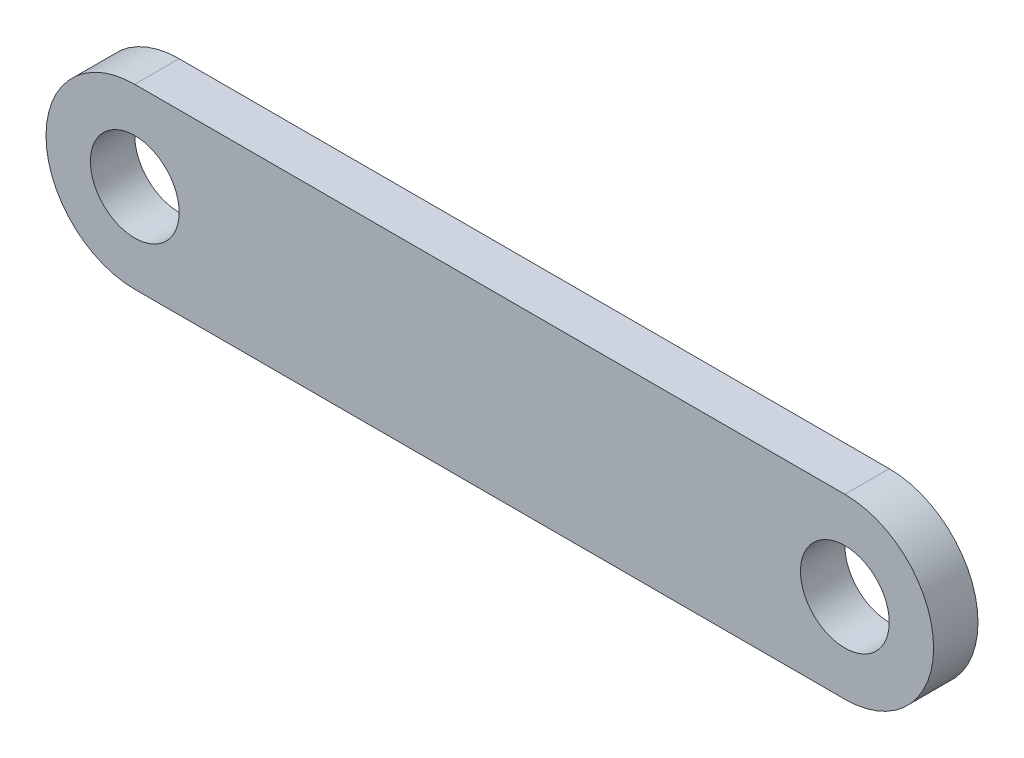
SolidWorks part; units mm, degrees
ref_plane "前视基准面" through (0, 0, 0) normal (0, 0, 1) x (1, 0, 0)
ref_plane "上视基准面" through (0, 0, 0) normal (0, 1, 0) x (1, 0, 0)
ref_plane "右视基准面" through (0, 0, 0) normal (1, 0, 0) x (0, 0, -1)
other "Configuration Table"
sketch "草图1" plane through (0, 0, 0) normal (0, 0, 1) x (1, 0, 0)
  line L0 (-44.3083, 27.0009) -> (115.6917, 27.0009) construction
  line L1 (-44.3083, 47.0009) -> (115.6917, 47.0009)
  line L2 (-44.3083, 7.0009) -> (115.6917, 7.0009)
  arc A0 (-44.3083, 47.0009) -> (-44.3083, 7.0009) centre (-44.3083, 27.0009) ccw
  arc A1 (115.6917, 7.0009) -> (115.6917, 47.0009) centre (115.6917, 27.0009) ccw
  circle A2 centre (115.6917, 27.0009) radius 10
  circle A3 centre (-44.3083, 27.0009) radius 10
  point P2 (35.6917, 27.0009)
  dimension "D2" = 20
  dimension "D1" = 160
extrude "凸台-拉伸1" add sketch "草图1" along normal blind 10
